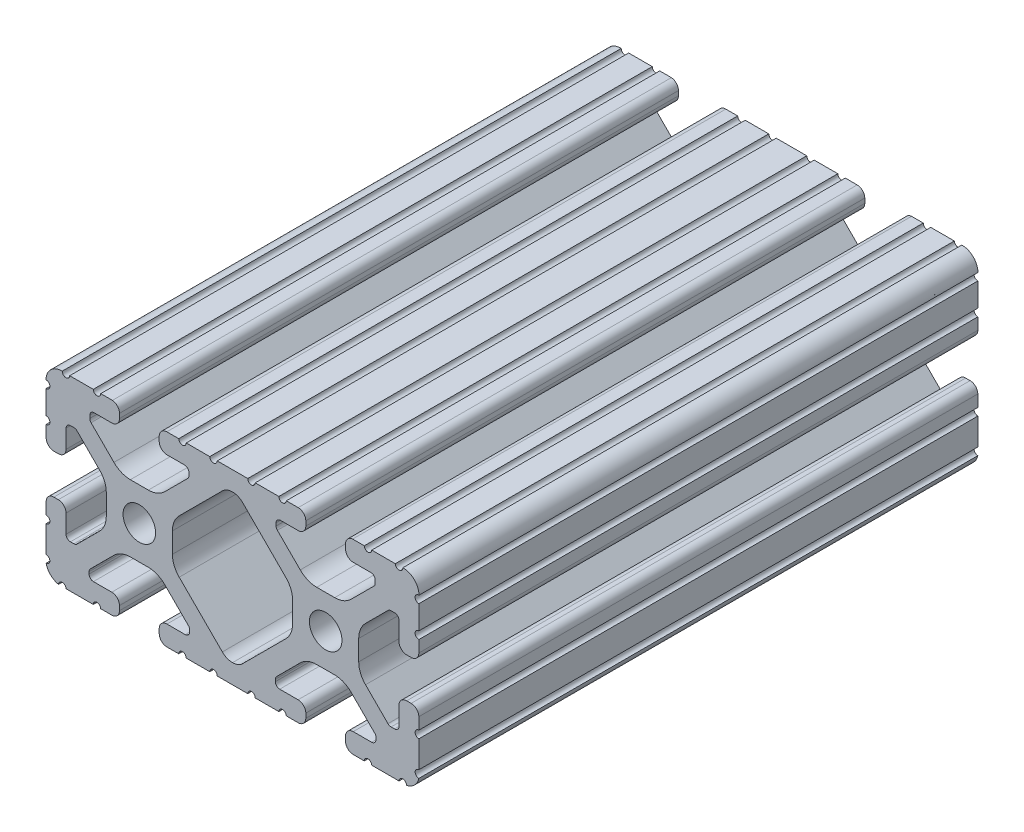
SolidWorks part; units mm, degrees
material "6005A-T61"
ref_plane "Front Plane" through (0, 0, 0) normal (0, 0, 1) x (1, 0, 0)
ref_plane "Top Plane" through (0, 0, 0) normal (0, 1, 0) x (1, 0, 0)
ref_plane "Right Plane" through (0, 0, 0) normal (1, 0, 0) x (0, 0, -1)
sketch "Sketch1" plane through (0, 0, 0) normal (0, 0, 1) x (1, 0, 0)
  line L0 (-3.1211, -19.05) -> (3.1211, -19.05)
  line L1 (-38.1, 10.287) -> (-38.1, 14.3752)
  line L2 (0, -34.5561) -> (0, 32.8014) construction
  line L3 (-38.1, 0) -> (0, 0) construction
  line L4 (-38.1, 9.5497) -> (-38.1, 10.287)
  line L5 (-19.05, 19.05) -> (-19.05, -20.2827) construction
  line L6 (0, -15.1247) -> (0, -15.1131) construction
  line L7 (9.1761, 12.9058) -> (13.8525, 8.2294)
  line L8 (8.9158, 14.097) -> (8.9158, 13.5344)
  line L9 (13.4112, 14.986) -> (9.8048, 14.986)
  line L10 (14.986, 17.4968) -> (14.986, 16.5608)
  line L11 (10.9975, 19.05) -> (13.4328, 19.05)
  line L12 (8.6331, 19.05) -> (9.4735, 19.05)
  line L13 (4.6451, 19.05) -> (8.6331, 19.05)
  line L14 (31.792, 10.0266) -> (27.1976, 5.4321)
  line L15 (33.147, 10.287) -> (32.4207, 10.287)
  line L16 (29.2071, 19.05) -> (33.2963, 19.05)
  line L17 (28.4698, 19.05) -> (29.2071, 19.05)
  line L18 (-38.1, 5.6388) -> (-38.1, 8.0257)
  line L19 (24.5589, 19.05) -> (26.9458, 19.05)
  line L20 (23.114, 16.5608) -> (23.114, 17.4806)
  line L21 (28.2952, 14.986) -> (24.6888, 14.986)
  line L22 (29.1842, 13.5344) -> (29.1842, 14.097)
  line L23 (-34.036, 9.398) -> (-34.036, 5.6388)
  line L24 (-35.6108, 4.064) -> (-36.5252, 4.064)
  line L25 (24.2475, 8.2294) -> (28.9239, 12.9058)
  line L26 (25.8064, -2.0735) -> (25.8064, 2.0735)
  line L27 (35.6108, 4.064) -> (36.5252, 4.064)
  line L28 (34.036, 9.398) -> (34.036, 5.6388)
  line L29 (38.1, 5.6388) -> (38.1, 8.0257)
  line L30 (38.1, 9.5497) -> (38.1, 10.287)
  line L31 (38.1, 10.287) -> (38.1, 14.3752)
  line L32 (17.2111, 6.8382) -> (20.8889, 6.8382)
  line L33 (2.077, 14.2576) -> (10.9024, 5.4321)
  line L34 (-31.792, -10.0266) -> (-27.1976, -5.4321)
  line L35 (-33.147, -10.287) -> (-32.4207, -10.287)
  line L36 (-29.2071, -19.05) -> (-34.0473, -19.05)
  line L37 (-28.4698, -19.05) -> (-29.2071, -19.05)
  line L38 (-24.6888, -19.05) -> (-26.9458, -19.05)
  line L39 (12.2936, -2.0735) -> (12.2936, 2.0735)
  line L40 (-23.114, -16.5608) -> (-23.114, -17.4752)
  line L41 (-28.448, -14.986) -> (-24.6888, -14.986)
  line L42 (-29.337, -13.6872) -> (-29.337, -14.097)
  line L43 (2.077, -14.2576) -> (10.9024, -5.4321)
  line L44 (-3.1211, 19.05) -> (3.1211, 19.05)
  line L45 (8.763, -14.097) -> (8.763, -13.6872)
  line L46 (-24.2475, -8.2294) -> (-29.0766, -13.0586)
  line L47 (-35.6108, -4.064) -> (-36.5252, -4.064)
  line L48 (-34.036, -9.398) -> (-34.036, -5.6388)
  line L49 (-38.1, -5.6388) -> (-38.1, -8.0257)
  line L50 (-38.1, -9.5497) -> (-38.1, -10.287)
  line L51 (-38.1, -10.287) -> (-38.1, -15.036)
  line L52 (17.2111, -6.8382) -> (20.8889, -6.8382)
  line L53 (38.1, -10.287) -> (38.1, -15.036)
  line L54 (38.1, -9.5497) -> (38.1, -10.287)
  line L55 (38.1, -5.6388) -> (38.1, -8.0257)
  line L56 (34.036, -9.398) -> (34.036, -5.6388)
  line L57 (35.6108, -4.064) -> (36.5252, -4.064)
  line L58 (24.2475, -8.2294) -> (29.0766, -13.0586)
  line L59 (29.337, -13.6872) -> (29.337, -14.097)
  line L60 (-17.2111, -6.8382) -> (-20.8889, -6.8382)
  line L61 (-9.0234, -13.0586) -> (-13.8525, -8.2294)
  line L62 (-8.763, -14.097) -> (-8.763, -13.6872)
  line L63 (-13.4112, -14.986) -> (-9.652, -14.986)
  line L64 (-14.986, -17.4752) -> (-14.986, -16.5608)
  line L65 (-10.9975, -19.05) -> (-13.4112, -19.05)
  line L66 (28.448, -14.986) -> (24.6888, -14.986)
  line L67 (23.114, -16.5608) -> (23.114, -17.4752)
  line L68 (24.6888, -19.05) -> (26.9458, -19.05)
  line L69 (28.4698, -19.05) -> (29.2071, -19.05)
  line L70 (29.2071, -19.05) -> (34.0473, -19.05)
  line L71 (-8.6331, -19.05) -> (-9.4735, -19.05)
  line L72 (33.147, -10.287) -> (32.4207, -10.287)
  line L73 (31.792, -10.0266) -> (27.1976, -5.4321)
  line L74 (-4.6451, -19.05) -> (-8.6331, -19.05)
  line L75 (9.0234, -13.0586) -> (13.8525, -8.2294)
  line L76 (13.4112, -14.986) -> (9.652, -14.986)
  line L77 (-2.077, -14.2576) -> (-10.9024, -5.4321)
  line L78 (14.986, -17.4752) -> (14.986, -16.5608)
  line L79 (10.9975, -19.05) -> (13.4112, -19.05)
  line L80 (4.6451, -19.05) -> (8.6331, -19.05)
  line L81 (8.6331, -19.05) -> (9.4735, -19.05)
  line L83 (-12.2936, -2.0735) -> (-12.2936, 2.0735)
  line L84 (-25.8064, -2.0735) -> (-25.8064, 2.0735)
  line L85 (-2.077, 14.2576) -> (-10.9024, 5.4321)
  line L87 (-4.6451, 19.05) -> (-8.6331, 19.05)
  line L88 (-8.6331, 19.05) -> (-9.4735, 19.05)
  line L89 (-10.9975, 19.05) -> (-13.4328, 19.05)
  line L90 (-14.986, 17.4968) -> (-14.986, 16.5608)
  line L91 (-13.4112, 14.986) -> (-9.8048, 14.986)
  line L92 (-8.9158, 14.097) -> (-8.9158, 13.5344)
  line L93 (-9.1761, 12.9058) -> (-13.8525, 8.2294)
  line L94 (-17.2111, 6.8382) -> (-20.8889, 6.8382)
  line L95 (-24.2475, 8.2294) -> (-28.9239, 12.9058)
  line L96 (-29.1842, 13.5344) -> (-29.1842, 14.097)
  line L97 (-28.2952, 14.986) -> (-24.6888, 14.986)
  line L98 (-23.114, 16.5608) -> (-23.114, 17.4806)
  line L99 (-24.5589, 19.05) -> (-26.9458, 19.05)
  line L100 (-28.4698, 19.05) -> (-29.2071, 19.05)
  line L101 (-29.2071, 19.05) -> (-33.2963, 19.05)
  line L109 (-33.147, 10.287) -> (-32.4207, 10.287)
  line L165 (-31.792, 10.0266) -> (-27.1976, 5.4321)
  arc A0 (-38.1376, 15.8983) -> (-38.1, 14.3752) centre (-38.1, 15.1372) cw
  arc A1 (-38.1, 9.5497) -> (-38.1, 8.0257) centre (-38.1, 8.7877) cw
  arc A2 (9.1761, 12.9058) -> (8.9158, 13.5344) centre (9.8048, 13.5344) cw
  arc A3 (8.9158, 14.097) -> (9.8048, 14.986) centre (9.8048, 14.097) cw
  arc A4 (-36.5252, 4.064) -> (-38.1, 5.6388) centre (-36.5252, 5.6388) cw
  arc A5 (14.986, 16.5608) -> (13.4112, 14.986) centre (13.4112, 16.5608) cw
  arc A6 (13.4328, 19.05) -> (14.986, 17.4968) centre (13.4328, 17.4968) cw
  arc A7 (10.9975, 19.05) -> (9.4735, 19.05) centre (10.2355, 19.05) cw
  arc A8 (4.6451, 19.05) -> (3.1211, 19.05) centre (3.8831, 19.05) cw
  arc A9 (0, 15.1131) -> (2.077, 14.2576) centre (0.0116, 12.1921) cw
  arc A10 (25.8064, 2.0735) -> (27.1976, 5.4321) centre (30.5562, 2.0735) cw
  arc A11 (31.792, 10.0266) -> (32.4207, 10.287) centre (32.4207, 9.398) cw
  arc A12 (33.147, 10.287) -> (34.036, 9.398) centre (33.147, 9.398) cw
  arc A13 (34.8195, 19.0968) -> (38.1376, 15.8983) centre (34.903, 15.8631) cw
  arc A14 (34.8195, 19.0968) -> (33.2963, 19.05) centre (34.0579, 19.0734) cw
  arc A15 (28.4698, 19.05) -> (26.9458, 19.05) centre (27.7078, 19.05) cw
  arc A16 (23.114, 17.4806) -> (24.5589, 19.05) centre (24.6888, 17.4806) cw
  arc A17 (24.6888, 14.986) -> (23.114, 16.5608) centre (24.6888, 16.5608) cw
  arc A18 (28.2952, 14.986) -> (29.1842, 14.097) centre (28.2952, 14.097) cw
  arc A19 (29.1842, 13.5344) -> (28.9239, 12.9058) centre (28.2952, 13.5344) cw
  arc A20 (-35.5713, -19.05) -> (-38.1, -16.56) centre (-34.9455, -15.8855) cw
  arc A21 (34.036, 5.6388) -> (35.6108, 4.064) centre (35.6108, 5.6388) ccw
  arc A22 (36.5252, 4.064) -> (38.1, 5.6388) centre (36.5252, 5.6388) ccw
  arc A23 (38.1, 9.5497) -> (38.1, 8.0257) centre (38.1, 8.7877) ccw
  arc A24 (24.2475, 8.2294) -> (20.8889, 6.8382) centre (20.8889, 11.588) cw
  arc A25 (17.2111, 6.8382) -> (13.8525, 8.2294) centre (17.2111, 11.588) cw
  arc A26 (10.9024, 5.4321) -> (12.2936, 2.0735) centre (7.5438, 2.0735) cw
  arc A27 (0, -15.1131) -> (2.077, -14.2576) centre (0.0116, -12.1921) ccw
  arc A28 (-34.036, 5.6388) -> (-35.6108, 4.064) centre (-35.6108, 5.6388) cw
  arc A29 (-25.8064, -2.0735) -> (-27.1976, -5.4321) centre (-30.5562, -2.0735) cw
  arc A30 (-31.792, -10.0266) -> (-32.4207, -10.287) centre (-32.4207, -9.398) cw
  arc A31 (-33.147, -10.287) -> (-34.036, -9.398) centre (-33.147, -9.398) cw
  arc A33 (-35.5713, -19.05) -> (-34.0473, -19.05) centre (-34.8093, -19.05) cw
  arc A34 (-28.4698, -19.05) -> (-26.9458, -19.05) centre (-27.7078, -19.05) cw
  arc A35 (10.9024, -5.4321) -> (12.2936, -2.0735) centre (7.5438, -2.0735) ccw
  circle A36 centre (19.05, 0) radius 3.3274
  arc A37 (-23.114, -17.4752) -> (-24.6888, -19.05) centre (-24.6888, -17.4752) cw
  arc A38 (-24.6888, -14.986) -> (-23.114, -16.5608) centre (-24.6888, -16.5608) cw
  arc A39 (-28.448, -14.986) -> (-29.337, -14.097) centre (-28.448, -14.097) cw
  arc A40 (-29.337, -13.6872) -> (-29.0766, -13.0586) centre (-28.448, -13.6872) cw
  arc A41 (-24.2475, -8.2294) -> (-20.8889, -6.8382) centre (-20.8889, -11.588) cw
  arc A42 (-34.036, -5.6388) -> (-35.6108, -4.064) centre (-35.6108, -5.6388) ccw
  arc A43 (-36.5252, -4.064) -> (-38.1, -5.6388) centre (-36.5252, -5.6388) ccw
  arc A44 (-38.1, -9.5497) -> (-38.1, -8.0257) centre (-38.1, -8.7877) ccw
  arc A45 (-38.1, -16.56) -> (-38.1, -15.036) centre (-38.1, -15.798) ccw
  arc A46 (38.1, -16.56) -> (38.1, -15.036) centre (38.1, -15.798) cw
  arc A47 (38.1, -9.5497) -> (38.1, -8.0257) centre (38.1, -8.7877) cw
  arc A48 (36.5252, -4.064) -> (38.1, -5.6388) centre (36.5252, -5.6388) cw
  arc A49 (34.036, -5.6388) -> (35.6108, -4.064) centre (35.6108, -5.6388) cw
  arc A50 (24.2475, -8.2294) -> (20.8889, -6.8382) centre (20.8889, -11.588) ccw
  arc A51 (29.337, -13.6872) -> (29.0766, -13.0586) centre (28.448, -13.6872) ccw
  arc A52 (28.448, -14.986) -> (29.337, -14.097) centre (28.448, -14.097) ccw
  arc A53 (24.6888, -14.986) -> (23.114, -16.5608) centre (24.6888, -16.5608) ccw
  arc A54 (-17.2111, -6.8382) -> (-13.8525, -8.2294) centre (-17.2111, -11.588) cw
  arc A55 (-9.0234, -13.0586) -> (-8.763, -13.6872) centre (-9.652, -13.6872) cw
  arc A56 (-8.763, -14.097) -> (-9.652, -14.986) centre (-9.652, -14.097) cw
  arc A57 (-14.986, -16.5608) -> (-13.4112, -14.986) centre (-13.4112, -16.5608) cw
  arc A58 (-13.4112, -19.05) -> (-14.986, -17.4752) centre (-13.4112, -17.4752) cw
  arc A59 (-10.9975, -19.05) -> (-9.4735, -19.05) centre (-10.2355, -19.05) cw
  arc A60 (-4.6451, -19.05) -> (-3.1211, -19.05) centre (-3.8831, -19.05) cw
  arc A61 (23.114, -17.4752) -> (24.6888, -19.05) centre (24.6888, -17.4752) ccw
  arc A62 (28.4698, -19.05) -> (26.9458, -19.05) centre (27.7078, -19.05) ccw
  arc A63 (35.5713, -19.05) -> (34.0473, -19.05) centre (34.8093, -19.05) ccw
  arc A64 (35.5713, -19.05) -> (38.1, -16.56) centre (34.9379, -15.8778) ccw
  arc A65 (33.147, -10.287) -> (34.036, -9.398) centre (33.147, -9.398) ccw
  arc A66 (31.792, -10.0266) -> (32.4207, -10.287) centre (32.4207, -9.398) ccw
  arc A67 (-10.9024, -5.4321) -> (-12.2936, -2.0735) centre (-7.5438, -2.0735) cw
  arc A68 (0, -15.1131) -> (-2.077, -14.2576) centre (-0.0116, -12.1921) cw
  arc A69 (0, 15.1131) -> (-2.077, 14.2576) centre (-0.0116, 12.1921) ccw
  arc A70 (-10.9024, 5.4321) -> (-12.2936, 2.0735) centre (-7.5438, 2.0735) ccw
  arc A71 (25.8064, -2.0735) -> (27.1976, -5.4321) centre (30.5562, -2.0735) ccw
  arc A72 (9.0234, -13.0586) -> (8.763, -13.6872) centre (9.652, -13.6872) ccw
  arc A73 (8.763, -14.097) -> (9.652, -14.986) centre (9.652, -14.097) ccw
  arc A74 (17.2111, -6.8382) -> (13.8525, -8.2294) centre (17.2111, -11.588) ccw
  arc A75 (13.4112, -19.05) -> (14.986, -17.4752) centre (13.4112, -17.4752) ccw
  arc A76 (14.986, -16.5608) -> (13.4112, -14.986) centre (13.4112, -16.5608) ccw
  arc A77 (-4.6451, 19.05) -> (-3.1211, 19.05) centre (-3.8831, 19.05) ccw
  arc A78 (-10.9975, 19.05) -> (-9.4735, 19.05) centre (-10.2355, 19.05) ccw
  arc A79 (-13.4328, 19.05) -> (-14.986, 17.4968) centre (-13.4328, 17.4968) ccw
  arc A80 (-14.986, 16.5608) -> (-13.4112, 14.986) centre (-13.4112, 16.5608) ccw
  arc A81 (-8.9158, 14.097) -> (-9.8048, 14.986) centre (-9.8048, 14.097) ccw
  arc A82 (-9.1761, 12.9058) -> (-8.9158, 13.5344) centre (-9.8048, 13.5344) ccw
  arc A83 (-17.2111, 6.8382) -> (-13.8525, 8.2294) centre (-17.2111, 11.588) ccw
  arc A84 (-24.2475, 8.2294) -> (-20.8889, 6.8382) centre (-20.8889, 11.588) ccw
  arc A85 (-29.1842, 13.5344) -> (-28.9239, 12.9058) centre (-28.2952, 13.5344) ccw
  arc A86 (-28.2952, 14.986) -> (-29.1842, 14.097) centre (-28.2952, 14.097) ccw
  arc A87 (-24.6888, 14.986) -> (-23.114, 16.5608) centre (-24.6888, 16.5608) ccw
  arc A88 (-23.114, 17.4806) -> (-24.5589, 19.05) centre (-24.6888, 17.4806) ccw
  arc A89 (-28.4698, 19.05) -> (-26.9458, 19.05) centre (-27.7078, 19.05) ccw
  arc A90 (-34.8195, 19.0968) -> (-33.2963, 19.05) centre (-34.0579, 19.0734) ccw
  arc A91 (-34.8195, 19.0968) -> (-38.1376, 15.8983) centre (-34.903, 15.8631) ccw
  arc A92 (4.6451, -19.05) -> (3.1211, -19.05) centre (3.8831, -19.05) ccw
  arc A93 (10.9975, -19.05) -> (9.4735, -19.05) centre (10.2355, -19.05) ccw
  arc A94 (38.1376, 15.8983) -> (38.1, 14.3752) centre (38.1, 15.1372) ccw
  arc A96 (-33.147, 10.287) -> (-34.036, 9.398) centre (-33.147, 9.398) ccw
  arc A97 (-31.792, 10.0266) -> (-32.4207, 10.287) centre (-32.4207, 9.398) ccw
  arc A98 (-25.8064, 2.0735) -> (-27.1976, 5.4321) centre (-30.5562, 2.0735) ccw
  circle A101 centre (-19.05, 0) radius 3.3274
  point P34 (0, 19.05)
  point P79 (25.6765, 0)
  point P274 (0, -19.05)
  point P282 (-25.6765, 0)
  point P283 (-12.2936, 0)
  dimension "D1" = 38.1
  dimension "D4" = 6.6548
  dimension "D10" = 4.064
  dimension "D2" = 76.2
  dimension "D3" = 38.1
  dimension "D5" = 8.128
  dimension "D6" = 20.574
  dimension "D7" = 12.2936
  dimension "D8" = 4.064
  dimension "D9" = 4.064
extrude "Extrude1" add sketch "Sketch1" against normal blind 114.3
